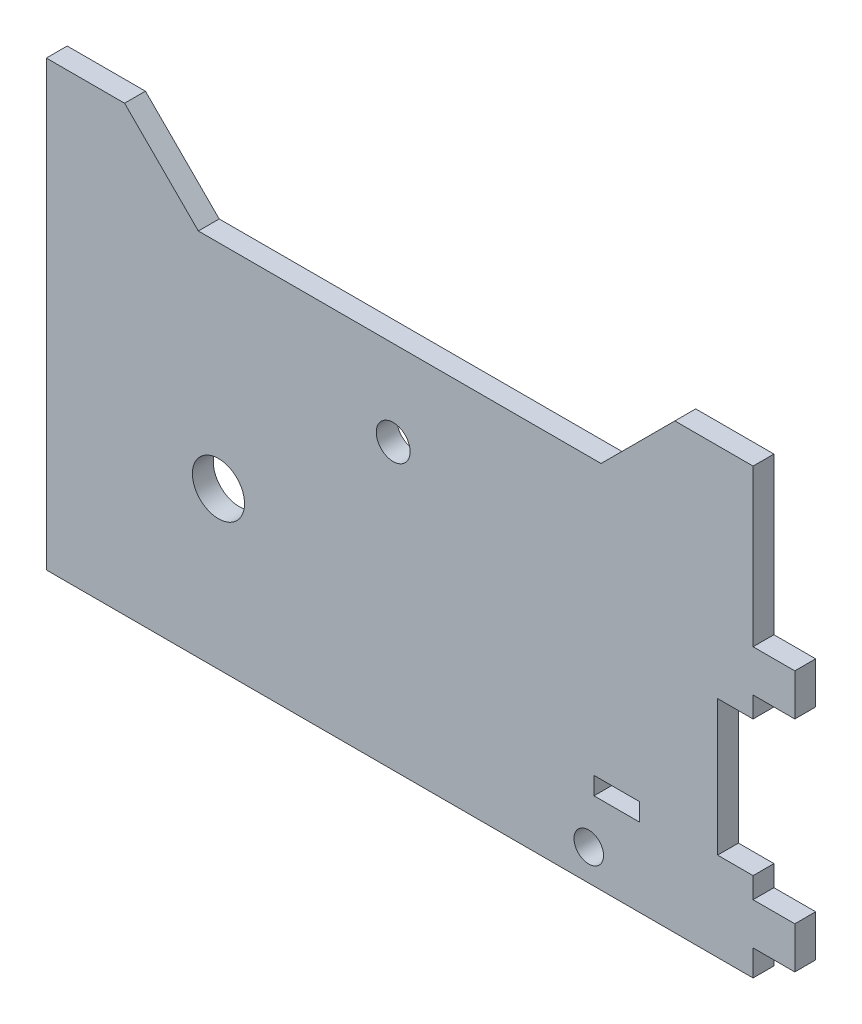
SolidWorks part; units mm, degrees
ref_plane "Front Plane" through (0, 0, 0) normal (0, 0, 1) x (1, 0, 0)
ref_plane "Top Plane" through (0, 0, 0) normal (0, 1, 0) x (1, 0, 0)
ref_plane "Right Plane" through (0, 0, 0) normal (1, 0, 0) x (0, 0, -1)
sketch "Sketch1" plane through (0, 0, 0) normal (0, 0, 1) x (1, 0, 0)
  line L0 (49, 30) -> (56.5, 30)
  line L1 (-79, -30) -> (49, -30)
  line L2 (-79, -30) -> (-79, 30)
  line L3 (-79, 30) -> (49, 30)
  line L6 (56.5, 13) -> (49.7, 13)
  line L7 (49.7, 13) -> (49.7, -13)
  line L8 (49.7, -13) -> (56.5, -13)
  line L10 (56.5, -30) -> (49, -30)
  line L11 (56.5, 30) -> (56.5, 13) construction
  line L12 (56.5, -13) -> (56.5, -30) construction
  line L13 (56.5, 30) -> (56.5, 25)
  line L14 (56.5, 25) -> (64.5, 25)
  line L15 (64.5, 25) -> (64.5, 17)
  line L16 (64.5, 17) -> (56.5, 17)
  line L17 (56.5, 17) -> (56.5, 13)
  line L18 (56.5, -13) -> (56.5, -17)
  line L19 (56.5, -17) -> (64.5, -17)
  line L20 (64.5, -17) -> (64.5, -25)
  line L21 (64.5, -25) -> (56.5, -25)
  line L22 (56.5, -25) -> (56.5, -30)
  line L23 (49, 30) -> (49, -30) construction
  line L24 (26, -11.6) -> (34.7, -11.6)
  line L25 (26, -11.6) -> (26, -15)
  line L26 (26, -15) -> (34.7, -15)
  line L27 (34.7, -11.6) -> (34.7, -15)
  circle A3 centre (-46, 0) radius 5
  circle A4 centre (25, -24) radius 2.83
  circle A5 centre (-12.5, 24.5) radius 3.25
  point P1 (-12, 0)
  dimension "D3" = 128
  dimension "D4" = 6
  dimension "D5" = 10
  dimension "D1" = 33
  dimension "D7" = 5
  dimension "D17" = 5.66
  dimension "D18" = 104
  dimension "D25" = 6.5
  dimension "D27" = 33.5
  dimension "D28" = 24.5
  dimension "D8" = 26
  dimension "D9" = 5
  dimension "D10" = 7.5
  dimension "D11" = 8
  dimension "D12" = 8
  dimension "D13" = 8.7
  dimension "D14" = 3.4
  dimension "D15" = 15
  dimension "D16" = 15
  dimension "D20" = 4
  dimension "D21" = 4
  dimension "D24" = 8
extrude "Boss-Extrude1" add sketch "Sketch1" along normal blind 4
sketch "Sketch2" plane through (0, 0, 0) normal (0, 0, 1) x (1, 0, 0)
  line L0 (-79, 30) -> (56.5, 30)
  line L1 (56.5, 30) -> (56.5, 55)
  line L2 (56.5, 55) -> (41.5, 55)
  line L3 (41.5, 55) -> (27.3579, 40.8579)
  line L4 (27.3579, 40.8579) -> (-49.8579, 40.8579)
  line L5 (-49.8579, 40.8579) -> (-64, 55)
  line L6 (-64, 55) -> (-79, 55)
  line L7 (-79, 55) -> (-79, 30)
  dimension "D1" = 25
  dimension "D2" = 15
  dimension "D3" = 20
  dimension "D4" = 135
extrude "Boss-Extrude2" add sketch "Sketch2" along normal blind 4
